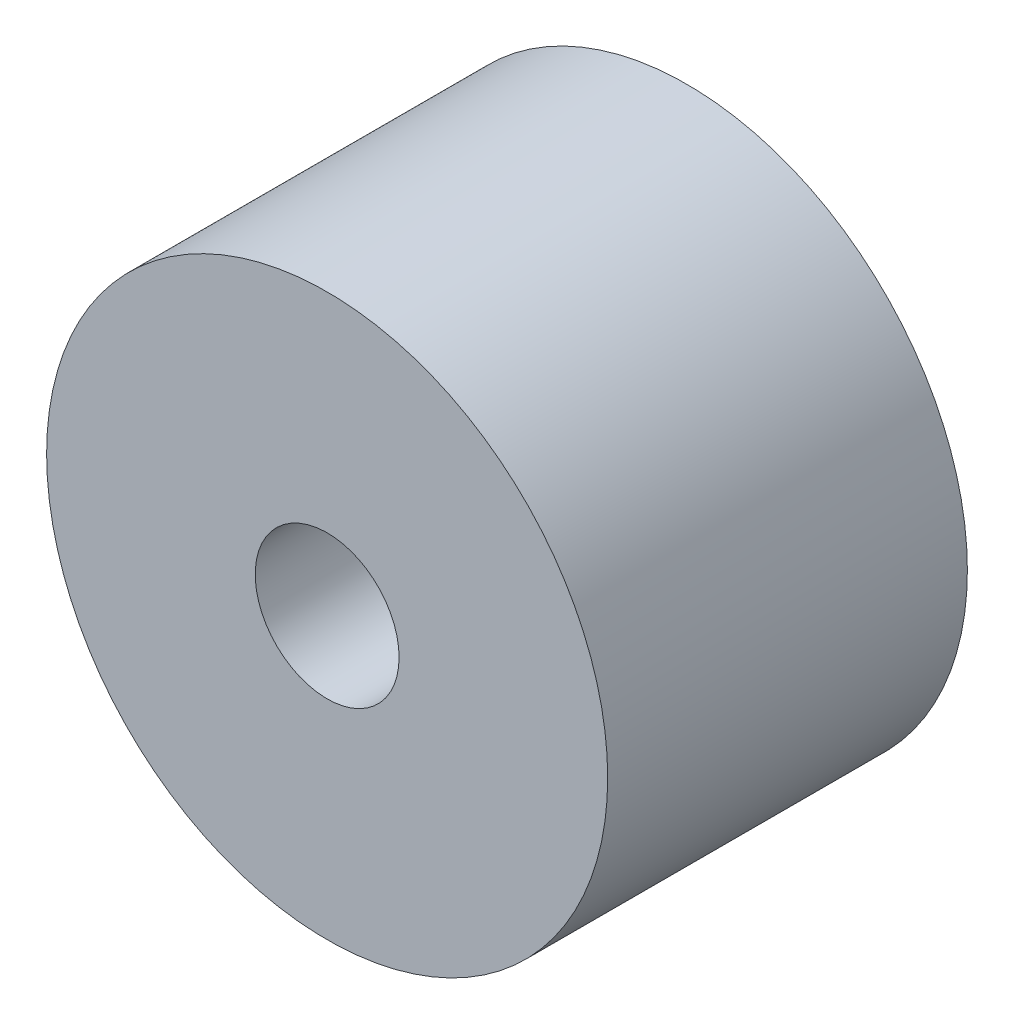
SolidWorks part; units mm, degrees
ref_plane "Front Plane" through (0, 0, 0) normal (0, 0, 1) x (1, 0, 0)
ref_plane "Top Plane" through (0, 0, 0) normal (0, 1, 0) x (1, 0, 0)
ref_plane "Right Plane" through (0, 0, 0) normal (1, 0, 0) x (0, 0, -1)
sketch "Sketch1" plane through (0, 0, 0) normal (0, 0, 1) x (1, 0, 0)
  circle A0 centre (0, 0) radius 19.5
  dimension "D1" = 39
extrude "Boss-Extrude1" add sketch "Sketch1" along normal mid plane 25 contours A0
sketch "Sketch2" plane through (0, 0, 12.5) normal (0, 0, 1) x (1, 0, 0)
  circle A0 centre (0, 0) radius 5
  dimension "D1" = 10
extrude "Cut-Extrude1" cut sketch "Sketch2" against normal blind 32
